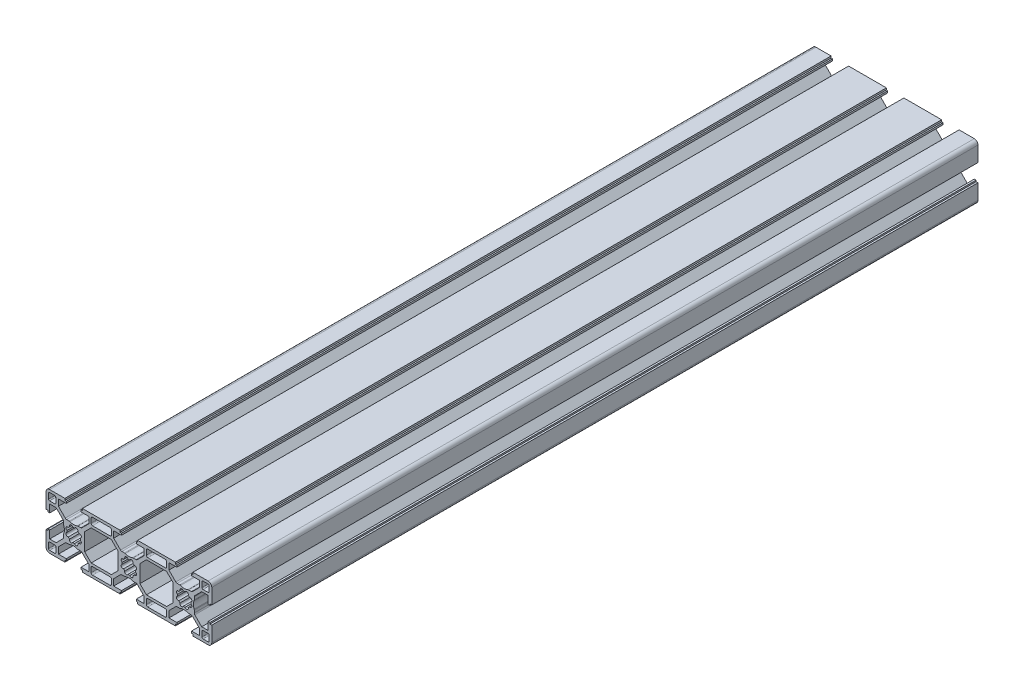
SolidWorks part; units mm, degrees
ref_plane "Piano frontale" through (0, 0, 0) normal (0, 0, 1) x (1, 0, 0)
ref_plane "Piano superiore" through (0, 0, 0) normal (0, 1, 0) x (1, 0, 0)
ref_plane "Piano destro" through (0, 0, 0) normal (1, 0, 0) x (0, 0, -1)
sketch "Model" plane through (0, 0, 0) normal (0, 0, 1) x (1, 0, 0)
  line L0 (209.6342, 131.2067) -> (208.0054, 131.2067)
  line L1 (200.3054, 131.2067) -> (198.6766, 131.2067)
  line L2 (193.6771, 133.6638) -> (197.4054, 129.9355)
  line L3 (197.4054, 129.9355) -> (197.4054, 126.4567)
  line L4 (197.4054, 126.4567) -> (193.1554, 126.4567)
  line L5 (193.1554, 126.4567) -> (193.1554, 125.4567)
  line L6 (193.1554, 125.4567) -> (193.9054, 125.4567)
  line L7 (193.9054, 125.4567) -> (193.9054, 124.4567)
  line L8 (193.9054, 124.4567) -> (214.4054, 124.4567)
  line L9 (214.4054, 124.4567) -> (214.4054, 125.4567)
  line L10 (214.4054, 125.4567) -> (215.1554, 125.4567)
  line L11 (215.1554, 125.4567) -> (215.1554, 126.4567)
  line L12 (215.1554, 126.4567) -> (210.9054, 126.4567)
  line L13 (210.9054, 126.4567) -> (210.9054, 129.9355)
  line L14 (210.9054, 129.9355) -> (214.6337, 133.6638)
  line L15 (215.3408, 133.9567) -> (216.7575, 133.9567)
  line L16 (221.5533, 133.9567) -> (222.97, 133.9567)
  line L17 (223.6771, 133.6638) -> (227.4054, 129.9355)
  line L18 (227.4054, 129.9355) -> (227.4054, 126.4567)
  line L19 (227.4054, 126.4567) -> (223.1554, 126.4567)
  line L20 (223.1554, 126.4567) -> (223.1554, 125.4567)
  line L21 (223.1554, 125.4567) -> (223.9054, 125.4567)
  line L22 (223.9054, 125.4567) -> (223.9054, 124.4567)
  line L23 (223.9054, 124.4567) -> (244.4054, 124.4567)
  line L24 (264.1554, 126.4567) -> (264.1554, 134.7067)
  line L25 (264.1554, 134.7067) -> (263.1554, 134.7067)
  line L26 (263.1554, 134.7067) -> (263.1554, 135.4567)
  line L27 (263.1554, 135.4567) -> (262.1554, 135.4567)
  line L28 (262.1554, 135.4567) -> (262.1554, 131.2067)
  line L29 (262.1554, 131.2067) -> (258.6766, 131.2067)
  line L30 (228.6766, 131.2067) -> (225.1554, 134.7279)
  line L31 (225.1554, 144.1855) -> (228.6766, 147.7067)
  line L32 (258.6766, 147.7067) -> (262.1554, 147.7067)
  line L33 (262.1554, 147.7067) -> (262.1554, 143.4567)
  line L34 (262.1554, 143.4567) -> (263.1554, 143.4567)
  line L35 (263.1554, 143.4567) -> (263.1554, 144.2067)
  line L36 (263.1554, 144.2067) -> (264.1554, 144.2067)
  line L37 (264.1554, 144.2067) -> (264.1554, 152.4567)
  line L38 (244.4054, 154.4567) -> (223.9054, 154.4567)
  line L39 (223.9054, 154.4567) -> (223.9054, 153.4567)
  line L40 (223.9054, 153.4567) -> (223.1554, 153.4567)
  line L41 (223.1554, 153.4567) -> (223.1554, 152.4567)
  line L42 (223.1554, 152.4567) -> (227.4054, 152.4567)
  line L43 (227.4054, 152.4567) -> (227.4054, 148.9779)
  line L44 (227.4054, 148.9779) -> (223.6771, 145.2496)
  line L45 (222.97, 144.9567) -> (221.5533, 144.9567)
  line L46 (216.7575, 144.9567) -> (215.3408, 144.9567)
  line L47 (214.6337, 145.2496) -> (210.9054, 148.9779)
  line L48 (210.9054, 148.9779) -> (210.9054, 152.4567)
  line L49 (210.9054, 152.4567) -> (215.1554, 152.4567)
  line L50 (215.1554, 152.4567) -> (215.1554, 153.4567)
  line L51 (215.1554, 153.4567) -> (214.4054, 153.4567)
  line L52 (214.4054, 153.4567) -> (214.4054, 154.4567)
  line L53 (214.4054, 154.4567) -> (193.9054, 154.4567)
  line L54 (193.9054, 154.4567) -> (193.9054, 153.4567)
  line L55 (193.9054, 153.4567) -> (193.1554, 153.4567)
  line L56 (193.1554, 153.4567) -> (193.1554, 152.4567)
  line L57 (193.1554, 152.4567) -> (197.4054, 152.4567)
  line L58 (197.4054, 152.4567) -> (197.4054, 148.9779)
  line L59 (197.4054, 148.9779) -> (193.6771, 145.2496)
  line L60 (192.97, 144.9567) -> (191.5533, 144.9567)
  line L61 (186.7575, 144.9567) -> (185.3408, 144.9567)
  line L62 (184.6337, 145.2496) -> (180.9054, 148.9779)
  line L63 (180.9054, 148.9779) -> (180.9054, 152.4567)
  line L64 (180.9054, 152.4567) -> (185.1554, 152.4567)
  line L65 (185.1554, 152.4567) -> (185.1554, 153.4567)
  line L66 (185.1554, 153.4567) -> (184.4054, 153.4567)
  line L67 (184.4054, 153.4567) -> (184.4054, 154.4567)
  line L68 (184.4054, 154.4567) -> (176.1554, 154.4567)
  line L69 (174.1554, 152.4567) -> (174.1554, 144.2067)
  line L70 (174.1554, 144.2067) -> (175.1554, 144.2067)
  line L71 (175.1554, 144.2067) -> (175.1554, 143.4567)
  line L72 (175.1554, 143.4567) -> (176.1554, 143.4567)
  line L73 (176.1554, 143.4567) -> (176.1554, 147.7067)
  line L74 (176.1554, 147.7067) -> (179.6342, 147.7067)
  line L75 (179.6342, 147.7067) -> (183.3625, 143.9784)
  line L76 (183.6554, 143.2713) -> (183.6554, 141.8546)
  line L77 (183.6554, 137.0588) -> (183.6554, 135.6421)
  line L78 (183.3625, 134.935) -> (179.6342, 131.2067)
  line L79 (179.6342, 131.2067) -> (176.1554, 131.2067)
  line L80 (176.1554, 131.2067) -> (176.1554, 135.4567)
  line L81 (176.1554, 135.4567) -> (175.1554, 135.4567)
  line L82 (175.1554, 135.4567) -> (175.1554, 134.7067)
  line L83 (175.1554, 134.7067) -> (174.1554, 134.7067)
  line L84 (174.1554, 134.7067) -> (174.1554, 126.4567)
  line L85 (176.1554, 124.4567) -> (184.4054, 124.4567)
  line L86 (184.4054, 124.4567) -> (184.4054, 125.4567)
  line L87 (184.4054, 125.4567) -> (185.1554, 125.4567)
  line L88 (185.1554, 125.4567) -> (185.1554, 126.4567)
  line L89 (185.1554, 126.4567) -> (180.9054, 126.4567)
  line L90 (180.9054, 126.4567) -> (180.9054, 129.9355)
  line L91 (180.9054, 129.9355) -> (184.6337, 133.6638)
  line L92 (185.3408, 133.9567) -> (186.7575, 133.9567)
  line L93 (191.5533, 133.9567) -> (192.97, 133.9567)
  line L94 (244.4054, 124.4567) -> (244.4054, 125.4567)
  line L95 (244.4054, 125.4567) -> (245.1554, 125.4567)
  line L96 (245.1554, 125.4567) -> (245.1554, 126.4567)
  line L97 (245.1554, 126.4567) -> (240.9054, 126.4567)
  line L98 (240.9054, 126.4567) -> (240.9054, 129.9355)
  line L99 (240.9054, 129.9355) -> (244.6337, 133.6638)
  line L100 (245.3408, 133.9567) -> (246.7575, 133.9567)
  line L101 (246.7575, 144.9567) -> (245.3408, 144.9567)
  line L102 (244.6337, 145.2496) -> (240.9054, 148.9779)
  line L103 (240.9054, 148.9779) -> (240.9054, 152.4567)
  line L104 (240.9054, 152.4567) -> (245.1554, 152.4567)
  line L105 (245.1554, 152.4567) -> (245.1554, 153.4567)
  line L106 (245.1554, 153.4567) -> (244.4054, 153.4567)
  line L107 (244.4054, 153.4567) -> (244.4054, 154.4567)
  line L108 (198.6766, 131.2067) -> (209.6342, 131.2067)
  line L109 (213.1554, 134.7279) -> (209.6342, 131.2067)
  line L110 (213.1554, 144.1855) -> (213.1554, 134.7279)
  line L111 (209.6342, 147.7067) -> (213.1554, 144.1855)
  line L112 (198.6766, 147.7067) -> (209.6342, 147.7067)
  line L113 (195.1554, 144.1855) -> (198.6766, 147.7067)
  line L114 (195.1554, 134.7279) -> (195.1554, 144.1855)
  line L115 (195.873, 134.0103) -> (195.1554, 134.7279)
  line L116 (198.6766, 131.2067) -> (195.873, 134.0103)
  line L117 (243.1554, 134.7279) -> (239.6342, 131.2067)
  line L118 (243.1554, 144.1855) -> (243.1554, 134.7279)
  line L119 (239.6342, 147.7067) -> (243.1554, 144.1855)
  line L120 (245.3408, 133.9567) -> (246.7575, 133.9567)
  line L121 (251.5533, 133.9567) -> (252.97, 133.9567)
  line L122 (253.6771, 133.6638) -> (257.4054, 129.9355)
  line L123 (258.6766, 131.2067) -> (254.9483, 134.935)
  line L124 (254.6554, 135.6421) -> (254.6554, 137.0588)
  line L125 (254.6554, 141.8546) -> (254.6554, 143.2713)
  line L126 (254.9483, 143.9784) -> (258.6766, 147.7067)
  line L127 (257.4054, 148.9779) -> (253.6771, 145.2496)
  line L128 (252.97, 144.9567) -> (251.5533, 144.9567)
  line L129 (262.1554, 154.4567) -> (253.9054, 154.4567)
  line L130 (253.9054, 154.4567) -> (253.9054, 153.4567)
  line L131 (253.9054, 153.4567) -> (253.1554, 153.4567)
  line L132 (253.1554, 153.4567) -> (253.1554, 152.4567)
  line L133 (253.1554, 152.4567) -> (257.4054, 152.4567)
  line L134 (257.4054, 152.4567) -> (257.4054, 148.9779)
  line L135 (228.6766, 131.2067) -> (239.6342, 131.2067)
  line L136 (257.4054, 129.9355) -> (257.4054, 126.4567)
  line L137 (257.4054, 126.4567) -> (253.1554, 126.4567)
  line L138 (253.1554, 126.4567) -> (253.1554, 125.4567)
  line L139 (253.1554, 125.4567) -> (253.9054, 125.4567)
  line L140 (253.9054, 125.4567) -> (253.9054, 124.4567)
  line L141 (253.9054, 124.4567) -> (262.1554, 124.4567)
  line L142 (225.1554, 134.7279) -> (225.1554, 144.1855)
  line L143 (228.6766, 147.7067) -> (239.6342, 147.7067)
  line L144 (208.9054, 149.0567) -> (199.4054, 149.0567)
  line L145 (209.7054, 152.2567) -> (209.7054, 149.8567)
  line L146 (199.4054, 153.0567) -> (208.9054, 153.0567)
  line L147 (198.6054, 149.8567) -> (198.6054, 152.2567)
  line L148 (238.9054, 149.0567) -> (229.4054, 149.0567)
  line L149 (239.7054, 152.2567) -> (239.7054, 149.8567)
  line L150 (229.4054, 153.0567) -> (238.9054, 153.0567)
  line L151 (228.6054, 149.8567) -> (228.6054, 152.2567)
  line L152 (208.9054, 129.8567) -> (199.4054, 129.8567)
  line L153 (198.6054, 129.0567) -> (198.6054, 126.6567)
  line L154 (199.4054, 125.8567) -> (208.9054, 125.8567)
  line L155 (209.7054, 126.6567) -> (209.7054, 129.0567)
  line L156 (238.9054, 129.8567) -> (229.4054, 129.8567)
  line L157 (228.6054, 129.0567) -> (228.6054, 126.6567)
  line L158 (229.4054, 125.8567) -> (238.9054, 125.8567)
  line L159 (239.7054, 126.6567) -> (239.7054, 129.0567)
  line L160 (258.8054, 126.4567) -> (258.8054, 129.2067)
  line L161 (262.1554, 125.8567) -> (259.4054, 125.8567)
  line L162 (262.7554, 129.2067) -> (262.7554, 126.4567)
  line L163 (259.4054, 129.8067) -> (262.1554, 129.8067)
  line L164 (258.8054, 149.7067) -> (258.8054, 152.4567)
  line L165 (262.1554, 149.1067) -> (259.4054, 149.1067)
  line L166 (262.7554, 152.4567) -> (262.7554, 149.7067)
  line L167 (259.4054, 153.0567) -> (262.1554, 153.0567)
  line L168 (179.5054, 152.4567) -> (179.5054, 149.7067)
  line L169 (176.1554, 153.0567) -> (178.9054, 153.0567)
  line L170 (175.5554, 149.7067) -> (175.5554, 152.4567)
  line L171 (178.9054, 149.1067) -> (176.1554, 149.1067)
  line L172 (179.5054, 129.2067) -> (179.5054, 126.4567)
  line L173 (176.1554, 129.8067) -> (178.9054, 129.8067)
  line L174 (175.5554, 126.4567) -> (175.5554, 129.2067)
  line L175 (178.9054, 125.8567) -> (176.1554, 125.8567)
  arc A0 (215.3408, 133.9567) -> (214.6337, 133.6638) centre (215.3408, 132.9567) ccw
  arc A1 (216.7575, 133.9567) -> (217.1571, 134.04) centre (216.7575, 134.9567) ccw
  arc A2 (221.1537, 134.04) -> (217.1571, 134.04) centre (219.1554, 129.4567) ccw
  arc A3 (221.1537, 134.04) -> (221.5533, 133.9567) centre (221.5533, 134.9567) ccw
  arc A4 (223.6771, 133.6638) -> (222.97, 133.9567) centre (222.97, 132.9567) ccw
  arc A5 (262.1554, 124.4567) -> (264.1554, 126.4567) centre (262.1554, 126.4567) ccw
  arc A6 (264.1554, 152.4567) -> (262.1554, 154.4567) centre (262.1554, 152.4567) ccw
  arc A7 (222.97, 144.9567) -> (223.6771, 145.2496) centre (222.97, 145.9567) ccw
  arc A8 (221.5533, 144.9567) -> (221.1537, 144.8733) centre (221.5533, 143.9567) ccw
  arc A9 (217.1571, 144.8733) -> (221.1537, 144.8733) centre (219.1554, 149.4567) ccw
  arc A10 (217.1571, 144.8733) -> (216.7575, 144.9567) centre (216.7575, 143.9567) ccw
  arc A11 (214.6337, 145.2496) -> (215.3408, 144.9567) centre (215.3408, 145.9567) ccw
  arc A12 (192.97, 144.9567) -> (193.6771, 145.2496) centre (192.97, 145.9567) ccw
  arc A13 (191.5533, 144.9567) -> (191.1537, 144.8733) centre (191.5533, 143.9567) ccw
  arc A14 (187.1571, 144.8733) -> (191.1537, 144.8733) centre (189.1554, 149.4567) ccw
  arc A15 (187.1571, 144.8733) -> (186.7575, 144.9567) centre (186.7575, 143.9567) ccw
  arc A16 (184.6337, 145.2496) -> (185.3408, 144.9567) centre (185.3408, 145.9567) ccw
  arc A17 (176.1554, 154.4567) -> (174.1554, 152.4567) centre (176.1554, 152.4567) ccw
  arc A18 (183.6554, 143.2713) -> (183.3625, 143.9784) centre (182.6554, 143.2713) ccw
  arc A19 (183.6554, 141.8546) -> (183.7387, 141.4549) centre (184.6554, 141.8546) ccw
  arc A20 (183.7387, 137.4584) -> (183.7387, 141.4549) centre (179.1554, 139.4567) ccw
  arc A21 (183.7387, 137.4584) -> (183.6554, 137.0588) centre (184.6554, 137.0588) ccw
  arc A22 (183.3625, 134.935) -> (183.6554, 135.6421) centre (182.6554, 135.6421) ccw
  arc A23 (174.1554, 126.4567) -> (176.1554, 124.4567) centre (176.1554, 126.4567) ccw
  arc A24 (185.3408, 133.9567) -> (184.6337, 133.6638) centre (185.3408, 132.9567) ccw
  arc A25 (186.7575, 133.9567) -> (187.1571, 134.04) centre (186.7575, 134.9567) ccw
  arc A26 (191.1537, 134.04) -> (187.1571, 134.04) centre (189.1554, 129.4567) ccw
  arc A27 (191.1537, 134.04) -> (191.5533, 133.9567) centre (191.5533, 134.9567) ccw
  arc A28 (193.6771, 133.6638) -> (192.97, 133.9567) centre (192.97, 132.9567) ccw
  arc A29 (245.3408, 133.9567) -> (244.6337, 133.6638) centre (245.3408, 132.9567) ccw
  arc A30 (246.7575, 133.9567) -> (247.1571, 134.04) centre (246.7575, 134.9567) ccw
  arc A31 (247.1571, 144.8733) -> (246.7575, 144.9567) centre (246.7575, 143.9567) ccw
  arc A32 (244.6337, 145.2496) -> (245.3408, 144.9567) centre (245.3408, 145.9567) ccw
  arc A33 (222.7725, 139.9455) -> (222.0587, 141.6687) centre (222.4156, 140.8071) ccw
  arc A34 (222.0587, 141.6687) -> (221.3674, 142.36) centre (219.1554, 139.4567) ccw
  arc A35 (221.3674, 142.36) -> (219.6442, 143.0738) centre (220.5058, 142.7169) ccw
  arc A36 (219.6442, 143.0738) -> (218.6666, 143.0738) centre (219.1554, 139.4567) ccw
  arc A37 (218.6666, 143.0738) -> (216.9434, 142.36) centre (217.805, 142.7169) ccw
  arc A38 (216.9434, 142.36) -> (216.252, 141.6687) centre (219.1554, 139.4567) ccw
  arc A39 (216.252, 141.6687) -> (215.5383, 139.9455) centre (215.8952, 140.8071) ccw
  arc A40 (215.5383, 139.9455) -> (215.5383, 138.9678) centre (219.1554, 139.4567) ccw
  arc A41 (215.5383, 138.9678) -> (216.252, 137.2447) centre (215.8952, 138.1062) ccw
  arc A42 (216.252, 137.2447) -> (216.9434, 136.5533) centre (219.1554, 139.4567) ccw
  arc A43 (216.9434, 136.5533) -> (218.6666, 135.8396) centre (217.805, 136.1964) ccw
  arc A44 (218.6666, 135.8396) -> (219.6442, 135.8396) centre (219.1554, 139.4567) ccw
  arc A45 (219.6442, 135.8396) -> (221.3674, 136.5533) centre (220.5058, 136.1964) ccw
  arc A46 (221.3674, 136.5533) -> (222.0587, 137.2447) centre (219.1554, 139.4567) ccw
  arc A47 (222.0587, 137.2447) -> (222.7725, 138.9678) centre (222.4156, 138.1062) ccw
  arc A48 (222.7725, 138.9678) -> (222.7725, 139.9455) centre (219.1554, 139.4567) ccw
  arc A49 (252.7725, 139.9455) -> (252.0587, 141.6687) centre (252.4156, 140.8071) ccw
  arc A50 (252.0587, 141.6687) -> (251.3674, 142.36) centre (249.1554, 139.4567) ccw
  arc A51 (251.3674, 142.36) -> (249.6442, 143.0738) centre (250.5058, 142.7169) ccw
  arc A52 (249.6442, 143.0738) -> (248.6666, 143.0738) centre (249.1554, 139.4567) ccw
  arc A53 (248.6666, 143.0738) -> (246.9434, 142.36) centre (247.805, 142.7169) ccw
  arc A54 (246.9434, 142.36) -> (246.252, 141.6687) centre (249.1554, 139.4567) ccw
  arc A55 (246.252, 141.6687) -> (245.5383, 139.9455) centre (245.8952, 140.8071) ccw
  arc A56 (245.5383, 139.9455) -> (245.5383, 138.9678) centre (249.1554, 139.4567) ccw
  arc A57 (245.5383, 138.9678) -> (246.252, 137.2447) centre (245.8952, 138.1062) ccw
  arc A58 (246.252, 137.2447) -> (246.9434, 136.5533) centre (249.1554, 139.4567) ccw
  arc A59 (246.9434, 136.5533) -> (248.6666, 135.8396) centre (247.805, 136.1964) ccw
  arc A60 (248.6666, 135.8396) -> (249.6442, 135.8396) centre (249.1554, 139.4567) ccw
  arc A61 (249.6442, 135.8396) -> (251.3674, 136.5533) centre (250.5058, 136.1964) ccw
  arc A62 (251.3674, 136.5533) -> (252.0587, 137.2447) centre (249.1554, 139.4567) ccw
  arc A63 (252.0587, 137.2447) -> (252.7725, 138.9678) centre (252.4156, 138.1062) ccw
  arc A64 (252.7725, 138.9678) -> (252.7725, 139.9455) centre (249.1554, 139.4567) ccw
  arc A65 (245.3408, 133.9567) -> (244.6337, 133.6638) centre (245.3408, 132.9567) ccw
  arc A66 (246.7575, 133.9567) -> (247.1571, 134.04) centre (246.7575, 134.9567) ccw
  arc A67 (251.1537, 134.04) -> (247.1571, 134.04) centre (249.1554, 129.4567) ccw
  arc A68 (251.1537, 134.04) -> (251.5533, 133.9567) centre (251.5533, 134.9567) ccw
  arc A69 (253.6771, 133.6638) -> (252.97, 133.9567) centre (252.97, 132.9567) ccw
  arc A70 (254.6554, 135.6421) -> (254.9483, 134.935) centre (255.6554, 135.6421) ccw
  arc A71 (254.6554, 137.0588) -> (254.5721, 137.4584) centre (253.6554, 137.0588) ccw
  arc A72 (254.5721, 141.4549) -> (254.5721, 137.4584) centre (259.1554, 139.4567) ccw
  arc A73 (254.5721, 141.4549) -> (254.6554, 141.8546) centre (253.6554, 141.8546) ccw
  arc A74 (254.9483, 143.9784) -> (254.6554, 143.2713) centre (255.6554, 143.2713) ccw
  arc A75 (252.97, 144.9567) -> (253.6771, 145.2496) centre (252.97, 145.9567) ccw
  arc A76 (251.5533, 144.9567) -> (251.1537, 144.8733) centre (251.5533, 143.9567) ccw
  arc A77 (247.1571, 144.8733) -> (251.1537, 144.8733) centre (249.1554, 149.4567) ccw
  arc A78 (247.1571, 144.8733) -> (246.7575, 144.9567) centre (246.7575, 143.9567) ccw
  arc A79 (192.7725, 139.9455) -> (192.0587, 141.6687) centre (192.4156, 140.8071) ccw
  arc A80 (192.0587, 141.6687) -> (191.3674, 142.36) centre (189.1554, 139.4567) ccw
  arc A81 (191.3674, 142.36) -> (189.6442, 143.0738) centre (190.5058, 142.7169) ccw
  arc A82 (189.6442, 143.0738) -> (188.6666, 143.0738) centre (189.1554, 139.4567) ccw
  arc A83 (188.6666, 143.0738) -> (186.9434, 142.36) centre (187.805, 142.7169) ccw
  arc A84 (186.9434, 142.36) -> (186.252, 141.6687) centre (189.1554, 139.4567) ccw
  arc A85 (186.252, 141.6687) -> (185.5383, 139.9455) centre (185.8952, 140.8071) ccw
  arc A86 (185.5383, 139.9455) -> (185.5383, 138.9678) centre (189.1554, 139.4567) ccw
  arc A87 (185.5383, 138.9678) -> (186.252, 137.2447) centre (185.8952, 138.1062) ccw
  arc A88 (186.252, 137.2447) -> (186.9434, 136.5533) centre (189.1554, 139.4567) ccw
  arc A89 (186.9434, 136.5533) -> (188.6666, 135.8396) centre (187.805, 136.1964) ccw
  arc A90 (188.6666, 135.8396) -> (189.6442, 135.8396) centre (189.1554, 139.4567) ccw
  arc A91 (189.6442, 135.8396) -> (191.3674, 136.5533) centre (190.5058, 136.1964) ccw
  arc A92 (191.3674, 136.5533) -> (192.0587, 137.2447) centre (189.1554, 139.4567) ccw
  arc A93 (192.0587, 137.2447) -> (192.7725, 138.9678) centre (192.4156, 138.1062) ccw
  arc A94 (192.7725, 138.9678) -> (192.7725, 139.9455) centre (189.1554, 139.4567) ccw
  arc A95 (208.9054, 149.0567) -> (209.7054, 149.8567) centre (208.9054, 149.8567) ccw
  arc A96 (209.7054, 152.2567) -> (208.9054, 153.0567) centre (208.9054, 152.2567) ccw
  arc A97 (199.4054, 153.0567) -> (198.6054, 152.2567) centre (199.4054, 152.2567) ccw
  arc A98 (198.6054, 149.8567) -> (199.4054, 149.0567) centre (199.4054, 149.8567) ccw
  arc A99 (238.9054, 149.0567) -> (239.7054, 149.8567) centre (238.9054, 149.8567) ccw
  arc A100 (239.7054, 152.2567) -> (238.9054, 153.0567) centre (238.9054, 152.2567) ccw
  arc A101 (229.4054, 153.0567) -> (228.6054, 152.2567) centre (229.4054, 152.2567) ccw
  arc A102 (228.6054, 149.8567) -> (229.4054, 149.0567) centre (229.4054, 149.8567) ccw
  arc A103 (199.4054, 129.8567) -> (198.6054, 129.0567) centre (199.4054, 129.0567) ccw
  arc A104 (198.6054, 126.6567) -> (199.4054, 125.8567) centre (199.4054, 126.6567) ccw
  arc A105 (208.9054, 125.8567) -> (209.7054, 126.6567) centre (208.9054, 126.6567) ccw
  arc A106 (209.7054, 129.0567) -> (208.9054, 129.8567) centre (208.9054, 129.0567) ccw
  arc A107 (229.4054, 129.8567) -> (228.6054, 129.0567) centre (229.4054, 129.0567) ccw
  arc A108 (228.6054, 126.6567) -> (229.4054, 125.8567) centre (229.4054, 126.6567) ccw
  arc A109 (238.9054, 125.8567) -> (239.7054, 126.6567) centre (238.9054, 126.6567) ccw
  arc A110 (239.7054, 129.0567) -> (238.9054, 129.8567) centre (238.9054, 129.0567) ccw
  arc A111 (258.8054, 126.4567) -> (259.4054, 125.8567) centre (259.4054, 126.4567) ccw
  arc A112 (262.1554, 125.8567) -> (262.7554, 126.4567) centre (262.1554, 126.4567) ccw
  arc A113 (262.7554, 129.2067) -> (262.1554, 129.8067) centre (262.1554, 129.2067) ccw
  arc A114 (259.4054, 129.8067) -> (258.8054, 129.2067) centre (259.4054, 129.2067) ccw
  arc A115 (258.8054, 149.7067) -> (259.4054, 149.1067) centre (259.4054, 149.7067) ccw
  arc A116 (262.1554, 149.1067) -> (262.7554, 149.7067) centre (262.1554, 149.7067) ccw
  arc A117 (262.7554, 152.4567) -> (262.1554, 153.0567) centre (262.1554, 152.4567) ccw
  arc A118 (259.4054, 153.0567) -> (258.8054, 152.4567) centre (259.4054, 152.4567) ccw
  arc A119 (179.5054, 152.4567) -> (178.9054, 153.0567) centre (178.9054, 152.4567) ccw
  arc A120 (176.1554, 153.0567) -> (175.5554, 152.4567) centre (176.1554, 152.4567) ccw
  arc A121 (175.5554, 149.7067) -> (176.1554, 149.1067) centre (176.1554, 149.7067) ccw
  arc A122 (178.9054, 149.1067) -> (179.5054, 149.7067) centre (178.9054, 149.7067) ccw
  arc A123 (179.5054, 129.2067) -> (178.9054, 129.8067) centre (178.9054, 129.2067) ccw
  arc A124 (176.1554, 129.8067) -> (175.5554, 129.2067) centre (176.1554, 129.2067) ccw
  arc A125 (175.5554, 126.4567) -> (176.1554, 125.8567) centre (176.1554, 126.4567) ccw
  arc A126 (178.9054, 125.8567) -> (179.5054, 126.4567) centre (178.9054, 126.4567) ccw
extrude "Estrusione-Estrusione1" add sketch "Model" against normal blind 416 contours A77 A31 L101 A32 L102 L103 L104 L105 L106 L107 L38 L39 L40 L41 L42 L43 L44 A7 L45 A8 A9 A10 L46 A11 L47 L48 L49 L50 L51 L52 L53 L54 L55 L56 L57 L58 L59 A12 L60 A13 A14 A15 L61 A16 L62 L63 L64 L65 L66 L67 L68
